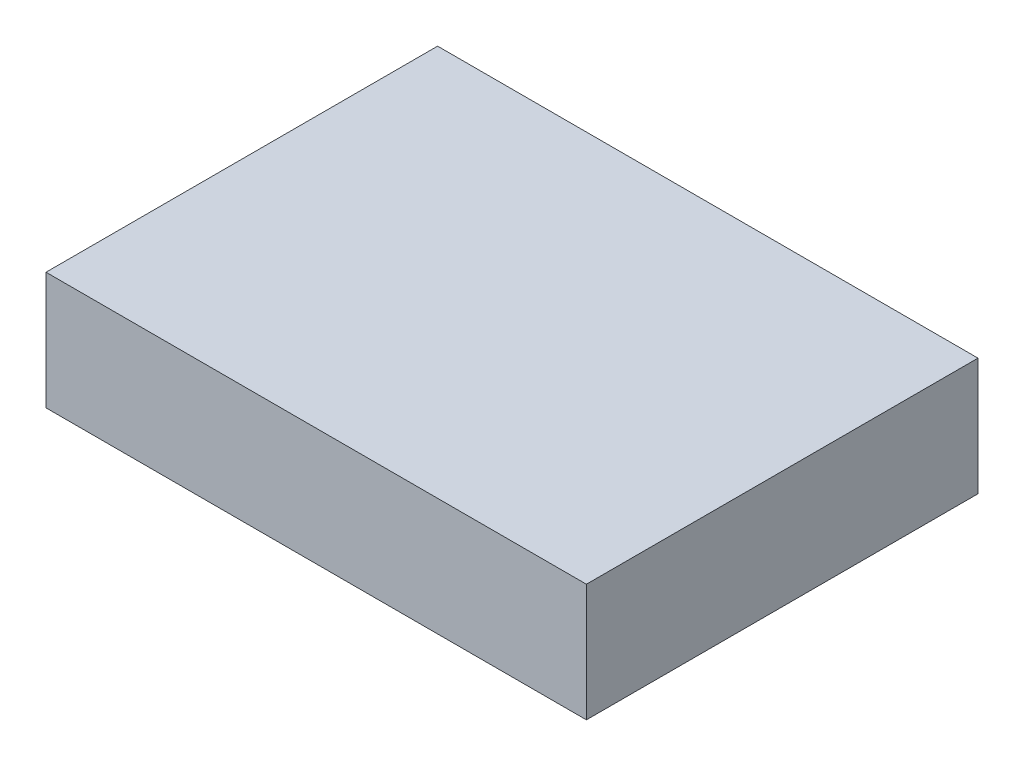
SolidWorks part; units mm, degrees
material "硅"
ref_plane "前视基准面" through (0, 0, 0) normal (0, 0, 1) x (1, 0, 0)
ref_plane "上视基准面" through (0, 0, 0) normal (0, 1, 0) x (1, 0, 0)
ref_plane "右视基准面" through (0, 0, 0) normal (1, 0, 0) x (0, 0, -1)
other "Configuration Table"
sketch "草图1" plane through (0, 0, 0) normal (0, 1, 0) x (1, 0, 0)
  line L1 (-34.5, -25) -> (34.5, -25)
  line L2 (-34.5, -25) -> (-34.5, 25)
  line L3 (-34.5, 25) -> (34.5, 25)
  line L4 (34.5, -25) -> (34.5, 25)
  line L5 (-34.5, -25) -> (34.5, 25) construction
  line L6 (-34.5, 25) -> (34.5, -25) construction
  point P0 (0, 0)
  dimension "D1" = 69
  dimension "D2" = 50
extrude "凸台-拉伸1" add sketch "草图1" along normal blind 15
